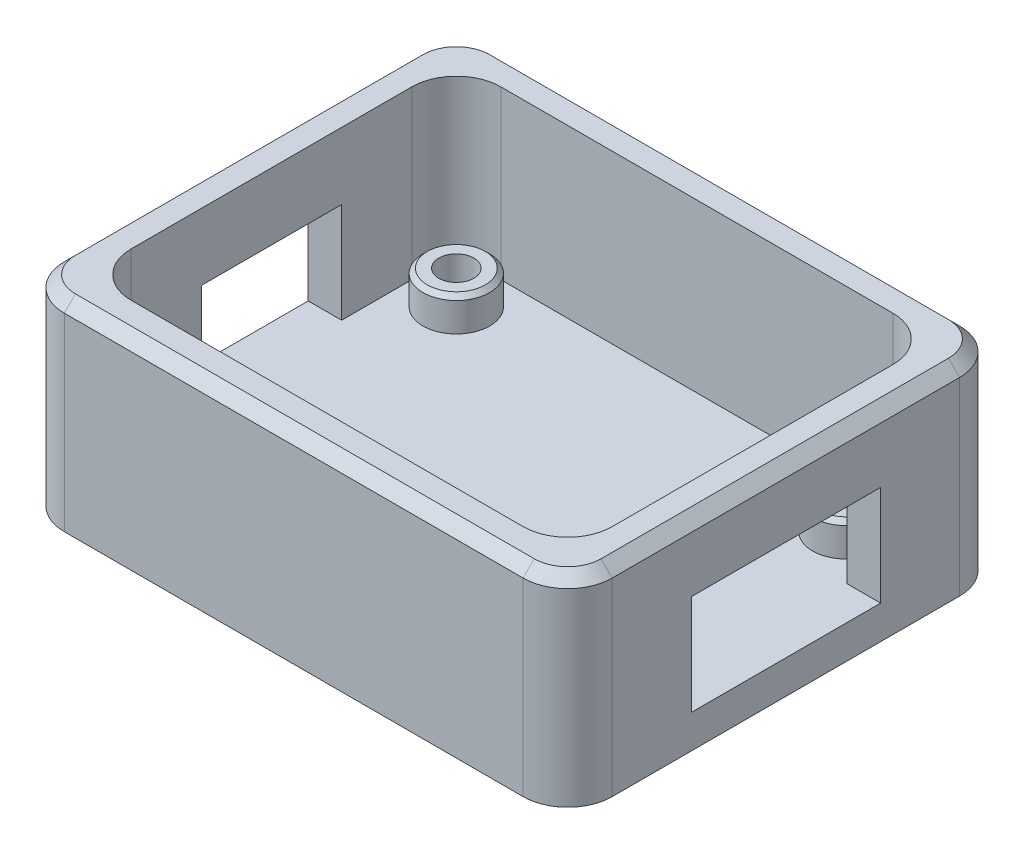
SolidWorks part; units mm, degrees
ref_plane "Front Plane" through (0, 0, 0) normal (0, 0, 1) x (1, 0, 0)
ref_plane "Top Plane" through (0, 0, 0) normal (0, 1, 0) x (1, 0, 0)
ref_plane "Right Plane" through (0, 0, 0) normal (1, 0, 0) x (0, 0, -1)
sketch "Sketch1" plane through (0, 0, 0) normal (0, 1, 0) x (1, 0, 0)
  line L0 (-3.81, 3.81) -> (58.674, 3.81)
  line L1 (0, 0) -> (54.864, 0)
  line L2 (0, 0) -> (0, -42.164)
  line L3 (0, -42.164) -> (54.864, -42.164)
  line L4 (54.864, 0) -> (54.864, -42.164)
  line L5 (58.674, 3.81) -> (58.674, -45.974)
  line L6 (-3.81, -45.974) -> (58.674, -45.974)
  line L7 (-3.81, 3.81) -> (-3.81, -45.974)
  dimension "D1" = 42.164
  dimension "D2" = 54.864
  dimension "D3" = 3.81
extrude "Boss-Extrude1" add sketch "Sketch1" along normal blind 19.05
ref_plane "Plane1" through (58.674, 0, 45.974) normal (0, 0, -1) x (-1, 0, 0)
sketch "Sketch3" plane through (0, 0, 0) normal (0, -1, 0) x (1, 0, 0)
  line L1 (-3.81, 45.974) -> (58.674, 45.974)
  line L2 (-3.81, 45.974) -> (-3.81, -3.81)
  line L3 (-3.81, -3.81) -> (58.674, -3.81)
  line L4 (58.674, 45.974) -> (58.674, -3.81)
extrude "Boss-Extrude2" add sketch "Sketch3" along normal blind 3.81 contours L2 L1 L4 L3
fillet "Fillet1" radius 5.08 4 edges at (54.864, 9.525, 42.164) (54.864, 9.525, 0) (0, 9.525, 42.164) (0, 9.525, 0)
sketch "Sketch4" plane through (0, 0, 0) normal (0, 1, 0) x (1, 0, 0)
  line L0 (49.784, 0) -> (5.08, 0) construction
  line L1 (5.207, -36.957) -> (49.657, -36.957) construction
  line L2 (5.207, -36.957) -> (5.207, -5.207) construction
  line L3 (5.207, -5.207) -> (49.657, -5.207) construction
  line L4 (49.657, -36.957) -> (49.657, -5.207) construction
  line L5 (0, -5.08) -> (0, -37.084) construction
  circle A0 centre (5.207, -5.207) radius 3.81
  circle A1 centre (5.207, -36.957) radius 3.81
  circle A2 centre (49.657, -36.957) radius 3.81
  circle A4 centre (49.657, -5.207) radius 3.81
  dimension "D5" = 7.62
  dimension "D1" = 31.75
  dimension "D2" = 44.45
  dimension "D3" = 5.207
  dimension "D4" = 5.207
extrude "Boss-Extrude3" add sketch "Sketch4" along normal blind 3.81 contours A4 | A2 | A1 | A0
hole_wizard "Ø4.0 (4) Diameter Hole1" positions "3DSketch1" profile "Sketch6" hole size "Ø4.0" standard "ANSI Metric"
sketch3d "3DSketch1"
  line L0 (5.207, 3.81, 5.207) -> (5.207, 0, 5.207) construction
  line L1 (5.207, 3.81, 36.957) -> (5.207, 0, 36.957) construction
  line L2 (49.657, 3.81, 36.957) -> (49.657, 0, 36.957) construction
  line L3 (49.657, 3.81, 5.207) -> (49.657, 0, 5.207) construction
  point P0 (5.207, 3.81, 5.207)
  point P4 (5.207, 3.81, 36.957)
  point P8 (49.657, 3.81, 36.957)
  point P14 (49.657, 3.81, 5.207)
sketch "Sketch6" plane through (5.207, 3.81, 5.207) normal (1, 0, 0) x (0, 0, 1)
  line L0 (0, 0) -> (0, 7.5517)
  line L1 (0, 7.5517) -> (2, 6.35)
  line L2 (2, 6.35) -> (2, 0)
  line L5 (2, 0) -> (0, 0)
  line L10 (0, 7.5517) -> (-2, 6.35) construction
  line L11 (0, -6.35) -> (0, 107.95) construction
  dimension "Hole Dia." = 4
  dimension "Hole Depth" = 6.35
  dimension "Drill Angle" = 118
sketch "Sketch8" plane through (58.674, 0, 0) normal (1, 0, 0) x (0, 0, -1)
  line L0 (3.81, -3.81) -> (-45.974, -3.81) construction
  line L1 (-31.877, 11.43) -> (-10.287, 11.43)
  line L2 (-31.877, 11.43) -> (-31.877, 0)
  line L3 (-31.877, 0) -> (-10.287, 0)
  line L4 (-10.287, 11.43) -> (-10.287, 0)
  line L5 (-31.877, 7.0729) -> (-45.974, 7.0729) construction
  line L6 (-45.974, 19.05) -> (-45.974, -3.81) construction
  line L7 (-10.287, 8.6111) -> (3.81, 8.6111) construction
  line L8 (3.81, 19.05) -> (3.81, -3.81) construction
  dimension "D1" = 3.81
  dimension "D2" = 21.59
  dimension "D3" = 11.43
extrude "Cut-Extrude1" cut sketch "Sketch8" against normal up to next contours L2 L1 L4 L3
sketch "Sketch9" plane through (-3.81, 0, 0) normal (-1, 0, 0) x (0, 0, 1)
  line L0 (45.974, -3.81) -> (-3.81, -3.81) construction
  line L1 (13.081, 11.43) -> (29.083, 11.43)
  line L2 (13.081, 11.43) -> (13.081, 0)
  line L3 (13.081, 0) -> (29.083, 0)
  line L4 (29.083, 11.43) -> (29.083, 0)
  line L5 (13.081, 4.8756) -> (-3.81, 4.8756) construction
  line L6 (-3.81, 19.05) -> (-3.81, -3.81) construction
  line L7 (29.083, 4.8756) -> (45.974, 4.8756) construction
  line L8 (45.974, 19.05) -> (45.974, -3.81) construction
  dimension "D1" = 11.43
  dimension "D2" = 16.002
  dimension "D3" = 3.81
extrude "Cut-Extrude2" cut sketch "Sketch9" against normal up to next contours L2 L1 L4 L3
fillet "Fillet2" radius 5.08 4 edges at (-3.81, 7.62, -3.81) (58.674, 7.62, -3.81) (58.674, 7.62, 45.974) (-3.81, 7.62, 45.974)
chamfer "Chamfer1" distance 1.27 angle 45 8 edges at (-2.3221, 19.05, -2.3221) (-3.81, 19.05, 21.082) (27.432, 19.05, -3.81) (-2.3221, 19.05, 44.4861) (57.1861, 19.05, -2.3221) (27.432, 19.05, 45.974) (58.674, 19.05, 21.082) (57.1861, 19.05, 44.4861)
chamfer "Chamfer2" distance 0.508 angle 45 4 edges at (5.207, 3.81, 9.017) (5.207, 3.81, 40.767) (49.657, 3.81, 40.767) (49.657, 3.81, 9.017)
